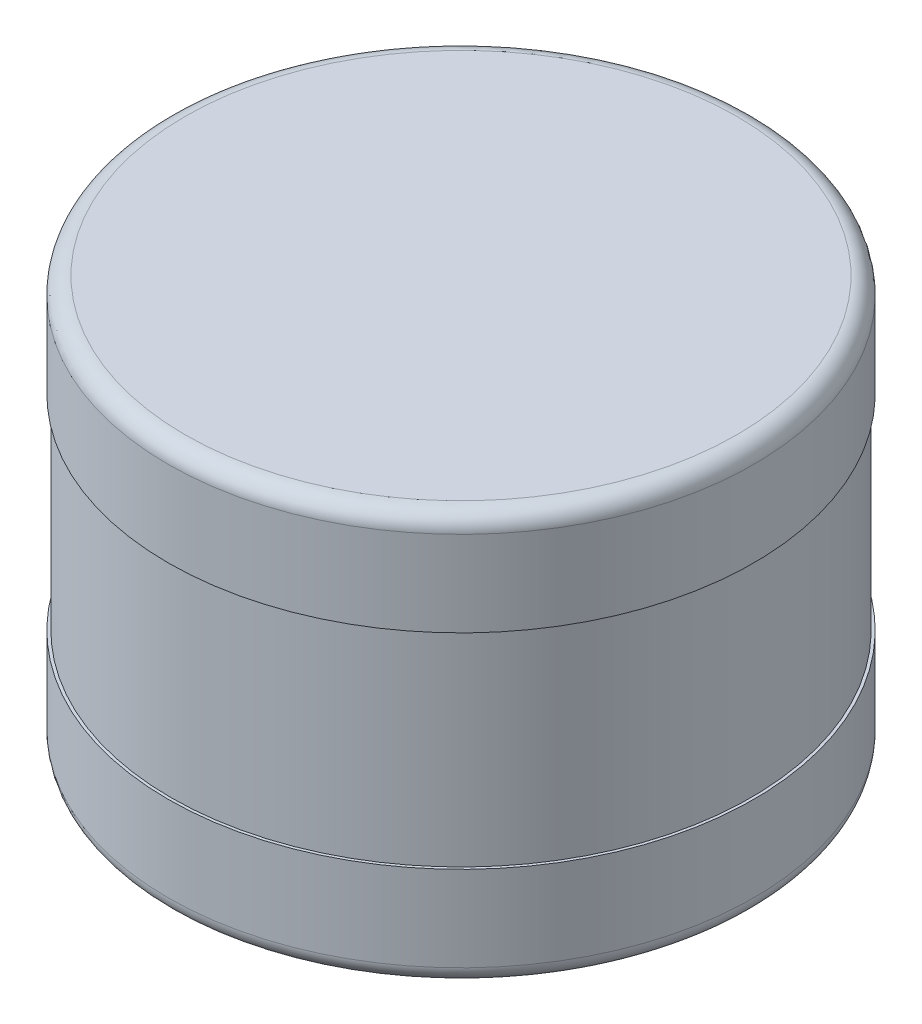
SolidWorks part; units mm, degrees
ref_plane "前视基准面" through (0, 0, 0) normal (0, 0, 1) x (1, 0, 0)
ref_plane "上视基准面" through (0, 0, 0) normal (0, 1, 0) x (1, 0, 0)
ref_plane "右视基准面" through (0, 0, 0) normal (1, 0, 0) x (0, 0, -1)
sketch "草图1" plane through (0, 0, 0) normal (0, 1, 0) x (1, 0, 0)
  circle A0 centre (0, 0) radius 51.5
extrude "凸台-拉伸1" add sketch "草图1" along normal blind 72
fillet "圆角1" radius 3 2 edges at (0, 0, 51.5) (0, 72, 51.5)
sketch "草图2" plane through (0, 0, 0) normal (0, 0, 1) x (1, 0, 0)
  line L0 (51.5, 36) -> (51.5, 54)
  line L1 (51.5, 3) -> (51.5, 69) construction
  line L2 (51.5, 54) -> (51, 54)
  line L3 (51, 54) -> (51, 18)
  line L4 (51, 18) -> (51.5, 18)
  line L5 (51.5, 18) -> (51.5, 36)
  line L6 (0, 0) -> (0, 77.9719) construction
revolve "切除-旋转1" cut sketch "草图2" angle 360 about L6
